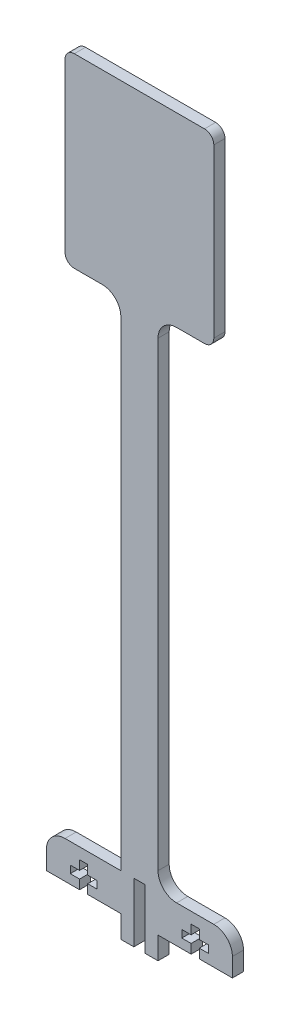
SolidWorks part; units mm, degrees
ref_plane "Front Plane" through (0, 0, 0) normal (0, 0, 1) x (1, 0, 0)
ref_plane "Top Plane" through (0, 0, 0) normal (0, 1, 0) x (1, 0, 0)
ref_plane "Right Plane" through (0, 0, 0) normal (1, 0, 0) x (0, 0, -1)
sketch "Sketch1" plane through (0, 0, 0) normal (0, 0, 1) x (1, 0, 0)
  line L0 (-5, -25) -> (-5, -159)
  line L7 (-5, -175) -> (-1.5, -175)
  line L8 (5, -175) -> (5, -169)
  line L10 (-5, -169) -> (-13.9, -169)
  line L11 (-25, -169) -> (-25, -159)
  line L12 (-25, -159) -> (-5, -159)
  line L13 (-16.1, -169) -> (-16.1, -166.5)
  line L14 (0, 25) -> (0, -175) construction
  line L15 (-16.1, -166.5) -> (-18.6, -166.5)
  line L16 (-18.6, -166.5) -> (-18.6, -164.5)
  line L17 (-18.6, -164.5) -> (-16.1, -164.5)
  line L18 (-16.1, -164.5) -> (-16.1, -162)
  line L19 (-16.1, -162) -> (-13.9, -162)
  line L20 (-13.9, -162) -> (-13.9, -164.5)
  line L21 (-13.9, -164.5) -> (-11.4, -164.5)
  line L22 (-11.4, -164.5) -> (-11.4, -166.5)
  line L23 (-11.4, -166.5) -> (-13.9, -166.5)
  line L24 (-13.9, -166.5) -> (-13.9, -169)
  line L25 (-15, -159) -> (-15, -169) construction
  line L26 (15, -159) -> (15, -169) construction
  line L27 (13.9, -166.5) -> (13.9, -169)
  line L28 (11.4, -166.5) -> (13.9, -166.5)
  line L29 (11.4, -164.5) -> (11.4, -166.5)
  line L30 (13.9, -164.5) -> (11.4, -164.5)
  line L31 (13.9, -162) -> (13.9, -164.5)
  line L32 (16.1, -162) -> (13.9, -162)
  line L33 (16.1, -164.5) -> (16.1, -162)
  line L34 (18.6, -164.5) -> (16.1, -164.5)
  line L35 (18.6, -166.5) -> (18.6, -164.5)
  line L36 (16.1, -166.5) -> (18.6, -166.5)
  line L37 (16.1, -169) -> (16.1, -166.5)
  line L38 (25, -159) -> (5, -159)
  line L39 (25, -169) -> (25, -159)
  line L40 (5, -169) -> (13.9, -169)
  line L41 (-16.1, -169) -> (-25, -169)
  line L42 (16.1, -169) -> (25, -169)
  line L43 (5, -159) -> (5, -25)
  line L44 (-5, -169) -> (-5, -175)
  line L45 (-1.5, -175) -> (-1.5, -159)
  line L46 (-1.5, -159) -> (1.5, -159)
  line L47 (1.5, -159) -> (1.5, -175)
  line L48 (1.5, -175) -> (5, -175)
  line L49 (0, 25) -> (-20, 25)
  line L50 (0, 25) -> (20, 25)
  line L51 (-5, -25) -> (5, -25) construction
  line L56 (-20, 25) -> (-20, -25)
  line L57 (-20, -25) -> (-5, -25)
  line L58 (20, 25) -> (20, -25)
  line L59 (20, -25) -> (5, -25)
  point P0 (0, 0)
  point P36 (-15, -162)
  point P57 (0, -159)
  dimension "D3" = 200
  dimension "D2" = 25
  dimension "D4" = 25
  dimension "D5" = 5
  dimension "D8" = 150
  dimension "D9" = 10
  dimension "D10" = 20
  dimension "D11" = 6
  dimension "D12" = 2.5
  dimension "D13" = 2
  dimension "D14" = 2.5
  dimension "D15" = 2.5
  dimension "D16" = 2.2
  dimension "D17" = 2.5
  dimension "D18" = 16
  dimension "D19" = 1.5
  dimension "D20" = 20
  dimension "D21" = 20
  dimension "D22" = 25
extrude "Boss-Extrude1" add sketch "Sketch1" along normal blind 3
fillet "Fillet1" radius 5 5 edges at (5, -159, 1.5) (25, -159, 1.5) (-25, -159, 1.5) (-5, -25, 1.5) (5, -25, 1.5)
fillet "Fillet2" radius 2.5 4 edges at (-20, 25, 1.5) (20, 25, 1.5) (20, -25, 1.5) (-20, -25, 1.5)
